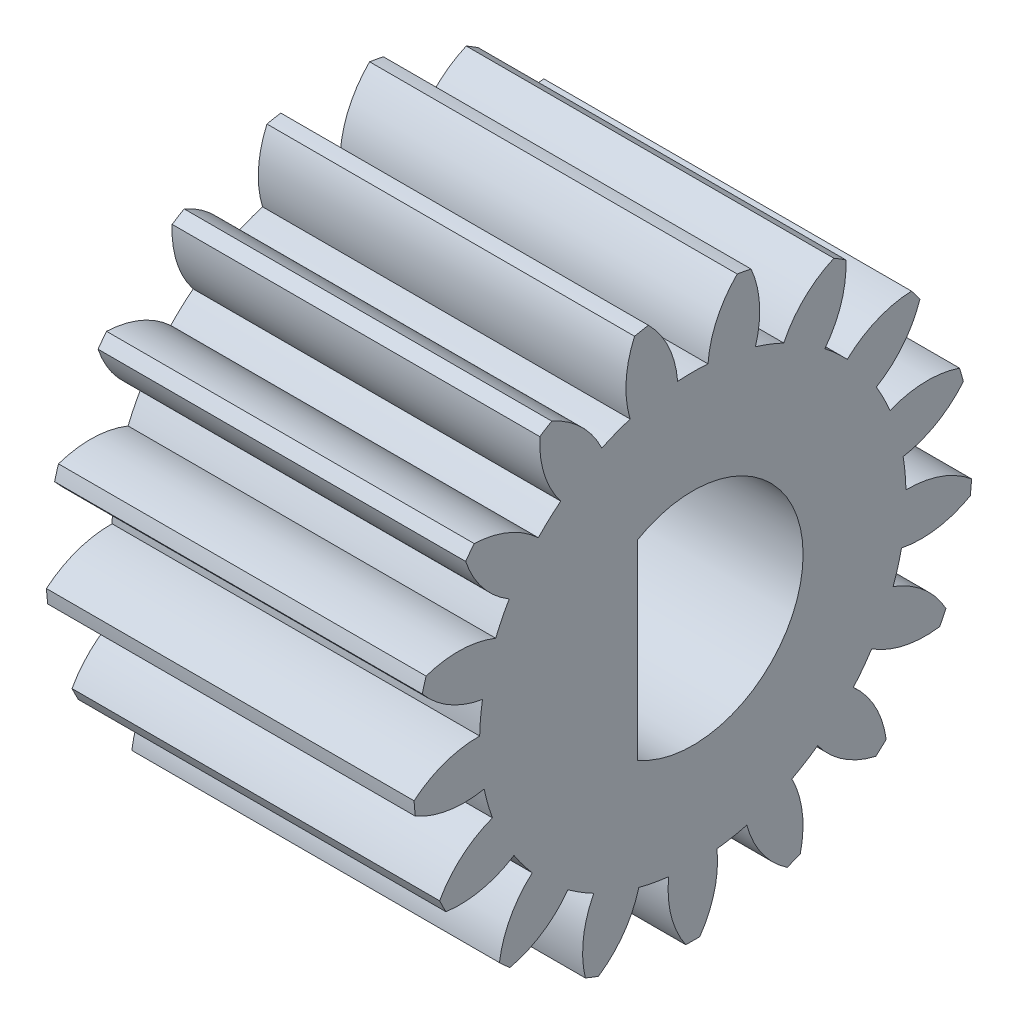
SolidWorks part; units mm, degrees
ref_plane "Plane1" through (0, 0, 0) normal (0, 0, 1) x (1, 0, 0)
ref_plane "Plane2" through (0, 0, 0) normal (0, 1, 0) x (1, 0, 0)
ref_plane "Plane3" through (0, 0, 0) normal (1, 0, 0) x (0, 0, -1)
sketch "HoldingSke" plane through (0, 0, 0) normal (0, 1, 0) x (1, 0, 0)
  line L0 (0, 0) -> (1.1954, -0.3655)
  line L1 (-15, 0) -> (100, 0) construction
  line L2 (0, 0) -> (-2.1039, 2.3779)
  line L3 (0, 0) -> (-11.863, 4.5341)
  line L4 (0, 0) -> (8.2586, 2.5249)
  line L5 (0, 0) -> (-46.8476, -17.4728)
  line L6 (0, 0) -> (-9.9476, -6.7116)
  line L7 (-2.1039, 2.3779) -> (8.6586, 51.2059)
  line L8 (-76.2, 54.61) -> (-75.2, 54.61)
  line L9 (-71.009, 38.7566) -> (-53.1078, 45.2721)
  line L10 (-76.2, 71.12) -> (104.1128, 71.12)
  line L11 (0, 0) -> (-12, 0)
  line L12 (-76.2, 101.6) -> (-76.17, 101.6)
  line L13 (24.9733, 27.94) -> (52.9518, 28.4284)
  line L14 (24.9733, 27.94) -> (24.9743, 27.94)
  line L15 (24.9733, 27.94) -> (100.4006, 29.5858)
  line L16 (-63.627, -0.8) -> (-12.827, -0.8)
  circle A0 centre (0, 0) radius 3
  circle A1 centre (0, 0) radius 5.799
  circle A2 centre (0, 0) radius 37.5
  circle A3 centre (0, 0) radius 3
  dimension "MHD" = 11.598
  dimension "Hub_dia" = 75
  dimension "Bore" = 6
  dimension "MBD" = 6
  dimension "Num_teeth" = 17
  dimension "Pitch" = 1.25
  dimension "Overall_len" = 50
  dimension "Show_teeth" = 17
  dimension "Thickness" = 12
  dimension "OAL" = 50.0001
  dimension "T_dim" = 1
  dimension "Ap" = 20
  dimension "H" = 19.05
  dimension "Pitch_radius" = 180.3128
  dimension "Width" = 12
  dimension "Backlash" = 0.03
  dimension "Addendum_fac" = 1
  dimension "Dedendum_fac" = 1.25
  dimension "Clearance_fac" = 0.25
  dimension "Dedendum_add" = 0.001
  dimension "Module" = 0.8
sketch "BasProSke" plane through (0, 0, 0) normal (0, 1, 0) x (1, 0, 0)
  line L0 (-10, 0) -> (60, 0) construction
  line L1 (0, 0) -> (0, 7.6)
  line L2 (0, 0) -> (10, 0)
  line L3 (10, 0) -> (10, 7.6)
  line L4 (10, 7.6) -> (0, 7.6)
  dimension "Thickness" = 10
  dimension "Diameter" = 15.2
revolve "Base-Revolve" add sketch "BasProSke" angle 360 about L0
sketch "TooCutSke" plane through (0, 0, 0) normal (1, 0, 0) x (0, 0, -1)
  line L1 (0, 0) -> (0, 107) construction
  line L2 (0, 0) -> (-0.6799, 6.7659) construction
  line L3 (0, 0) -> (-2.49, 13.3206) construction
  line L4 (-0.6799, 6.7659) -> (-1.245, 6.6603) construction
  arc A0 (0.4129, 5.7843) -> (-0.4129, 5.7843) centre (0, 0) ccw
  arc A1 (1.2302, 7.5255) -> (-1.2302, 7.5255) centre (0, 0) ccw
  circle A2 centre (0, 0) radius 6.8 construction
  circle A3 centre (0, 0) radius 6.3899 construction
  arc A4 (-0.4129, 5.7843) -> (-1.2302, 7.5255) centre (-3.1247, 5.5738) ccw
  arc A5 (1.2302, 7.5255) -> (0.4129, 5.7843) centre (3.1247, 5.5738) ccw
  dimension "Root_dia" = 11.598
  dimension "Overcut_dia" = 15.2508
  dimension "Pitch_dia" = 13.6
  dimension "Base_dia" = 12.7798
  dimension "Flank_rad" = 2.72
  dimension "Half_ang" = 10.588
  dimension "Half_CT" = 0.5749
extrude "ToothCut" cut sketch "TooCutSke" along normal through all
fillet "Breaks" [suppressed] radius 0.016
fillet "RootFillets" [suppressed] radius 0.201
pattern_circular "TeethCuts" count 17 every 21.176 about axis through (-10, 0, 0) along (1, 0, 0) of "ToothCut", "RootFillets", "Breaks"
sketch "HubNeaOneSke" plane through (0, 0, 0) normal (-1, 0, 0) x (0, 0, 1)
  circle A0 centre (0, 0) radius 5.799
  dimension "Diameter" = 11.598
extrude "HubNearOne" [suppressed] add sketch "HubNeaOneSke" along normal blind 40.0001
sketch "HubNeaBotSke" plane through (0, 0, 0) normal (-1, 0, 0) x (0, 0, 1)
  circle A0 centre (0, 0) radius 5.799
  dimension "Diameter" = 11.598
extrude "HubNearBoth" [suppressed] add sketch "HubNeaBotSke" along normal blind 20.0001
ref_plane "FarPln" through (10, 0, 0) normal (1, 0, 0) x (0, 0, -1)
sketch "HubFarSke" plane through (10, 0, 0) normal (1, 0, 0) x (0, 0, -1)
  circle A0 centre (0, 0) radius 5.799
  dimension "Diameter" = 11.598
extrude "HubFar" [suppressed] add sketch "HubFarSke" along normal blind 20.0001
sketch "BorSke" plane through (0, 0, 0) normal (1, 0, 0) x (0, 0, -1)
  circle A0 centre (0, 0) radius 3
  dimension "Diameter" = 6
extrude "Bore" cut sketch "BorSke" along normal mid plane 100.0002
sketch "KeySke" plane through (0, 0, 0) normal (1, 0, 0) x (0, 0, -1)
  line L0 (-1, 0) -> (-1, 4)
  line L1 (-1, 4) -> (1, 4)
  line L2 (1, 4) -> (1, 0)
  line L3 (0, 0) -> (0, 34) construction
  line L4 (-1, 0) -> (1, 0)
  dimension "Offset" = 4
  dimension "Width" = 2
extrude "Keyway" [suppressed] cut sketch "KeySke" along normal mid plane 100.0002
pattern_circular "Keyway2" [suppressed] count 2 every 90 about axis through (-10, 0, 0) along (1, 0, 0)
sketch "Sketch1" plane through (10, 0, 0) normal (1, 0, 0) x (0, 0, -1)
  line L0 (-3, 0) -> (-1.5, 0) construction
  line L1 (-1.5, 2.5981) -> (-1.5, -2.5981)
  circle A0 centre (0, 0) radius 3 construction
  arc A1 (-1.5, 2.5981) -> (-1.5, -2.5981) centre (0, 0) ccw
extrude "Boss-Extrude3" add sketch "Sketch1" against normal blind 10 contours L0 A1 L1 | A1 L0 L1
equation "' \"Module@HoldingSke\" = 6.35"
equation "' \"Num_teeth@HoldingSke\" = 12"
equation "' \"Ap@HoldingSke\" =  20"
equation "' \"Ap@HoldingSke\" = 20"
equation "' \"Width@HoldingSke\" = 0.5 * 25.4"
equation "' \"Hub_dia@HoldingSke\"= 1 * 25.4"
equation "' \"Hub_dia@HoldingSke\" = 1 * 25.4"
equation "' \"Overall_len@HoldingSke\" = 1.0 * 25.4"
equation "' \"Bore@HoldingSke\" = 0.75 * 25.4"
equation "' \"T_dim@HoldingSke\" = 0.1 * 25.4"
equation "' \"Width@KeySke\" = 0.25 * 25.4"
equation "' \"Show_teeth@HoldingSke\" = 13"
equation "' \"Backlash@HoldingSke\" = 0.009 * 25.4"
equation "' \"Addendum_fac@HoldingSke\" = 1.0"
equation "' \"Dedendum_fac@HoldingSke\" = 1.25"
equation "' \"Dedendum_add@HoldingSke\" = 0.00005 * 25.4"
equation "' \"Clearance_fac@HoldingSke\" = 0.25"
equation "\"Pitch@HoldingSke\" = 1 / \"Module@HoldingSke\""
equation "\"Overcut_dia@TooCutSke\" = (\"Num_teeth@HoldingSke\" + 2 * \"Addendum_fac@HoldingSke\") / \"Pitch@HoldingSke\" + 0.002 * 25.4"
equation "\"Pitch_dia@TooCutSke\" = \"Num_teeth@HoldingSke\" / \"Pitch@HoldingSke\""
equation "\"Base_dia@TooCutSke\" = \"Num_teeth@HoldingSke\" / \"Pitch@HoldingSke\" * cos((\"Ap@HoldingSke\"  * 3.14159265 / 180))"
equation "\"Root_dia@TooCutSke\" = (\"Num_teeth@HoldingSke\" + 2) / \"Pitch@HoldingSke\" - 2 * (\"Addendum_fac@HoldingSke\" + \"Dedendum_fac@HoldingSke\") / \"Pitch@HoldingSke\" - \"Dedendum_add@HoldingSke\" * 2"
equation "\"Half_ang@TooCutSke\" = 180 / \"Num_teeth@HoldingSke\""
equation "\"Half_CT@TooCutSke\" = \"Num_teeth@HoldingSke\" / \"Pitch@HoldingSke\" * sin((3.14159265 / 2 / \"Num_teeth@HoldingSke\")) / 2 - 7 * \"Backlash@HoldingSke\" / 4"
equation "\"Flank_rad@TooCutSke\" = \"Num_teeth@HoldingSke\" / \"Pitch@HoldingSke\" / 5"
equation "\"Radius@RootFillets\" = \"Clearance_fac@HoldingSke\" / \"Pitch@HoldingSke\" + \"Dedendum_add@HoldingSke\""
equation "\"Break_rad@Breaks\" = 0.02 / \"Pitch@HoldingSke\""
equation "\"Thickness@HoldingSke\" = \"Width@HoldingSke\""
equation "\"OAL@HoldingSke\" = \"Thickness@HoldingSke\""
equation "\"MHD@HoldingSke\" = (\"Num_teeth@HoldingSke\" + 2) / \"Pitch@HoldingSke\" - 2 * (\"Addendum_fac@HoldingSke\" + \"Dedendum_fac@HoldingSke\")  / \"Pitch@HoldingSke\" - \"Dedendum_add@HoldingSke\" * 2"
equation "\"MBD@HoldingSke\" = (\"Num_teeth@HoldingSke\" + 2) / \"Pitch@HoldingSke\" - 2 * (\"Addendum_fac@HoldingSke\" + \"Dedendum_fac@HoldingSke\")  / \"Pitch@HoldingSke\" - \"Dedendum_add@HoldingSke\" * 2 - 0.002 * 25.4"
equation "\"MHD@HoldingSke\" = ((sgn( \"MHD@HoldingSke\" - \"Hub_dia@HoldingSke\" )-1)*( \"MHD@HoldingSke\" - \"Hub_dia@HoldingSke\" ))/-2+ \"Hub_dia@HoldingSke\""
equation "\"MBD@HoldingSke\" = ((sgn( \"MBD@HoldingSke\" - \"Bore@HoldingSke\" )-1)*( \"MBD@HoldingSke\" - \"Bore@HoldingSke\" ))/-2+ \"Bore@HoldingSke\""
equation "\"OAL@HoldingSke\" = ((sgn( \"OAL@HoldingSke\" - \"Overall_len@HoldingSke\" )+1)*( \"OAL@HoldingSke\" - \"Overall_len@HoldingSke\" ))/2 + \"Overall_len@HoldingSke\" + 0.000002 * 25.4"
equation "\"Num_teeth@TeethCuts\" = int( \"Show_teeth@HoldingSke\" ) + 1"
equation "\"Num_teeth@TeethCuts\" = ((sgn( \"Num_teeth@TeethCuts\" - \"Num_teeth@HoldingSke\" )-1)*( \"Num_teeth@TeethCuts\" - \"Num_teeth@HoldingSke\" ))/-2+ \"Num_teeth@HoldingSke\""
equation "\"Num_teeth@TeethCuts\" = ((sgn( \"Num_teeth@TeethCuts\" - 2.0)+1)*( \"Num_teeth@TeethCuts\" - 2.0))/2 +2.0"
equation "\"Angle@TeethCuts\" = 360.0 / \"Num_teeth@HoldingSke\""
equation "\"Diameter@BasProSke\" = (\"Num_teeth@HoldingSke\" + 2 * \"Addendum_fac@HoldingSke\") / \"Pitch@HoldingSke\""
equation "\"Thickness@BasProSke\"= 10"
equation "' \"Fillet_rad@BasProSke\" =  \"Thickness@HoldingSke\" * 0.05"
equation "' \"Fillet_rad@BasProSke\" = \"Thickness@HoldingSke\" * 0.05"
equation "\"MHD@HoldingSke\" = ((sgn( \"MHD@HoldingSke\" - \"Root_dia@TooCutSke\" )-1)*( \"MHD@HoldingSke\" - \"Root_dia@TooCutSke\" ))/-2+ \"Root_dia@TooCutSke\""
equation "\"Diameter@HubNeaOneSke\" = \"MHD@HoldingSke\""
equation "\"Length@HubNearOne\" = \"OAL@HoldingSke\" - \"Thickness@BasProSke\""
equation "\"Diameter@HubNeaBotSke\" = \"MHD@HoldingSke\""
equation "\"Length@HubNearBoth\" = ( \"OAL@HoldingSke\" - \"Thickness@BasProSke\" ) / 2.0"
equation "\"Thickness@FarPln\" = \"Thickness@BasProSke\""
equation "\"Diameter@HubFarSke\" = \"MHD@HoldingSke\""
equation "\"Length@HubFar\" = ( \"OAL@HoldingSke\" - \"Thickness@BasProSke\" ) / 2.0"
equation "\"Diameter@BorSke\" = \"MBD@HoldingSke\""
equation "\"D1@Bore\" = \"OAL@HoldingSke\" * 2.0"
equation "\"D1@Keyway\" = \"OAL@HoldingSke\" * 2.0"
equation "\"Offset@KeySke\" = \"T_dim@HoldingSke\" + \"MBD@HoldingSke\" / 2.0"
